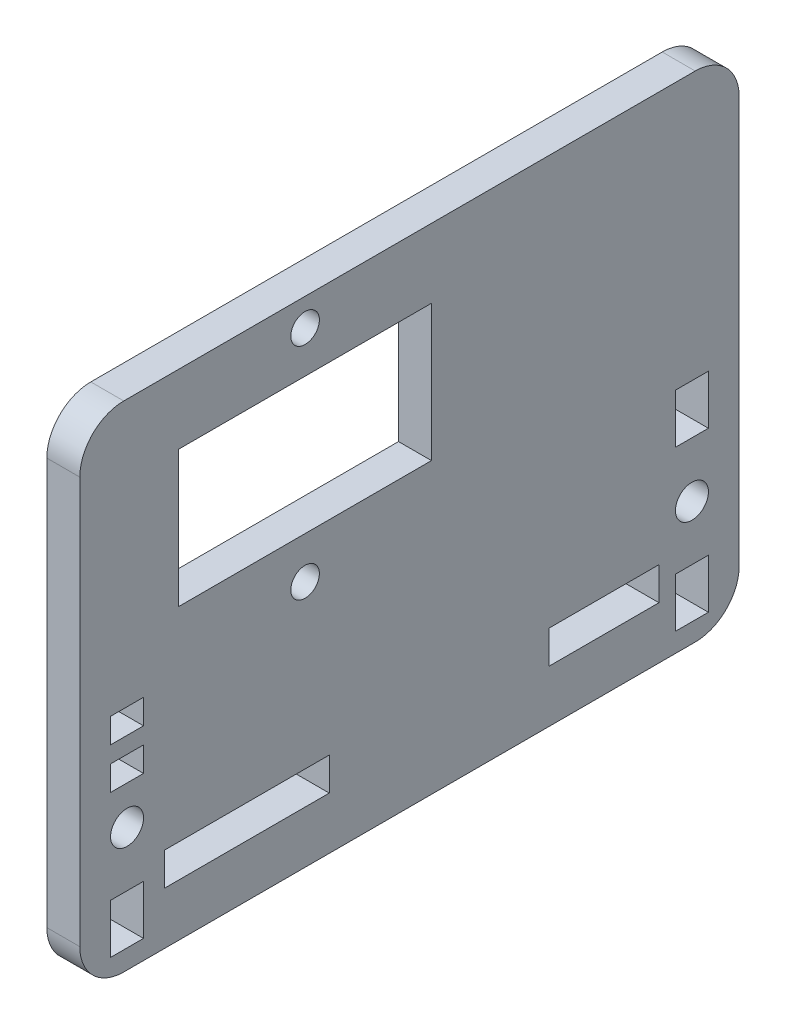
SolidWorks part; units mm, degrees
material "Acrílico (médio-alto impacto)"
ref_plane "Plano frontal" through (0, 0, 0) normal (0, 0, 1) x (1, 0, 0)
ref_plane "Plano superior" through (0, 0, 0) normal (0, 1, 0) x (1, 0, 0)
ref_plane "Plano direito" through (0, 0, 0) normal (1, 0, 0) x (0, 0, -1)
sketch "Esboço1" plane through (0, 0, 0) normal (1, 0, 0) x (0, 0, -1)
  line L1 (-30, -22.5) -> (30, -22.5)
  line L2 (-30, -22.5) -> (-30, 22.5)
  line L3 (-30, 22.5) -> (30, 22.5)
  line L4 (30, -22.5) -> (30, 22.5)
  point P7 (0, -22.5)
  point P9 (-30, 0)
  dimension "D1" = 45
  dimension "D2" = 60
sketch "Esboço9" plane through (0, 0, 0) normal (1, 0, 0) x (0, 0, -1)
  line L0 (-27.2, -18.5) -> (-24.2, -18.5) construction
  line L1 (-27.2, -20.75) -> (-24.2, -20.75)
  line L2 (-27.2, -20.75) -> (-27.2, -16.25)
  line L3 (-27.2, -16.25) -> (-24.2, -16.25)
  line L4 (-24.2, -20.75) -> (-24.2, -16.25)
  line L5 (-30, -22.5) -> (30, -22.5) construction
  line L7 (-25.7, -18.5) -> (-25.7, -11.25) construction
  line L8 (-25.7, -11.25) -> (-13.1725, -11.25) construction
  line L9 (-27.2, -1.75) -> (-24.2, -1.75)
  line L10 (-27.2, -1.75) -> (-27.2, -4)
  line L11 (-27.2, -4) -> (-24.2, -4)
  line L12 (-24.2, -1.75) -> (-24.2, -4)
  line L13 (0, 0) -> (0, -28.8435) construction
  line L14 (-27.2, -5.5) -> (-24.2, -5.5)
  line L15 (-27.2, -5.5) -> (-27.2, -7.75)
  line L16 (-27.2, -7.75) -> (-24.2, -7.75)
  line L17 (-24.2, -5.5) -> (-24.2, -7.75)
  line L18 (24.2, -16.25) -> (27.2, -16.25)
  line L19 (24.2, -16.25) -> (24.2, -20.75)
  line L20 (24.2, -20.75) -> (27.2, -20.75)
  line L21 (27.2, -16.25) -> (27.2, -20.75)
  line L22 (24.2, -1.75) -> (27.2, -1.75)
  line L23 (24.2, -1.75) -> (24.2, -6.25)
  line L24 (24.2, -6.25) -> (27.2, -6.25)
  line L25 (27.2, -1.75) -> (27.2, -6.25)
  point P24 (25.7, -11.25)
  dimension "D1" = 3
  dimension "D2" = 4.5
  dimension "D3" = 51.4
  dimension "D4" = 11.25
  dimension "D5" = 19
  dimension "D6" = 2.25
  dimension "D7" = 6
  dimension "D8" = 4.5
sketch "Esboço6" plane through (0, 0, 0) normal (1, 0, 0) x (0, 0, -1)
  line L0 (-24, -17.75) -> (24, -17.75) construction
  line L1 (-7.3, -14.75) -> (-22.3, -14.75)
  line L2 (-7.3, -14.75) -> (-7.3, -17.75)
  line L3 (-7.3, -17.75) -> (-22.3, -17.75)
  line L4 (-22.3, -14.75) -> (-22.3, -17.75)
  line L5 (22.7, -14.75) -> (12.7, -14.75)
  line L6 (22.7, -14.75) -> (22.7, -17.75)
  line L7 (22.7, -17.75) -> (12.7, -17.75)
  line L8 (12.7, -14.75) -> (12.7, -17.75)
  line L12 (0, 0) -> (0, -28.8435) construction
  line L14 (24.2, -20.75) -> (27.2, -20.75) construction
  line L15 (-16, -17.75) -> (-16, 10.2147) construction
  point P13 (0, -17.75)
  dimension "D1" = 3
  dimension "D2" = 1.7
  dimension "D3" = 15
  dimension "D4" = 10
  dimension "D5" = 1.3
  dimension "D6" = 48
  dimension "D7" = 7.3
  dimension "D8" = 12.7
  dimension "D9" = 3
  dimension "D10" = 8
ref_plane "Posicionamento base" through (0, -17.75, 0) normal (0, -1, 0) x (0, 0, -1)
extrude "Ressalto-extrusão1" add sketch "Esboço1" along normal blind 3
hole_wizard "Furo de diâmetro Ø3.0 (3)1" positions "Esboço7" profile "Esboço8" hole size "Ø3.0" standard "ISO" end condition through all
sketch "Esboço7" plane through (3, 0, 0) normal (1, 0, 0) x (0, 0, -1)
  point P0 (-25.7, -11.25)
  point P11 (25.7, -11.25)
sketch "Esboço8" plane through (3, -11.25, 25.7) normal (0, 1, 0) x (0, 0, -1)
  line L0 (0, 0) -> (0, 3)
  line L1 (0, 3) -> (1.5, 3)
  line L2 (1.5, 3) -> (1.5, 0)
  line L5 (1.5, 0) -> (0, 0)
  line L11 (0, -6.35) -> (0, 107.95) construction
  dimension "Thru Hole Dia." = 3
  dimension "Thru Hole Depth" = 3
extrude "Corte-extrusão2" cut sketch "Esboço9" along normal through all contours L11 L12 L9 L10 | L14 L17 L16 L15 | L4 L3 L2 L1
sketch "Perfil Corte" plane through (3, -11.3231, -32.0169) normal (1, 0, 0) x (0, 0, -1)
  line L0 (-41.5169, 11.3231) -> (-41.5169, 31.3231) construction
  line L1 (-53.0169, 15.1231) -> (-30.0169, 15.1231)
  line L2 (-53.0169, 15.1231) -> (-53.0169, 27.5231)
  line L3 (-53.0169, 27.5231) -> (-30.0169, 27.5231)
  line L4 (-30.0169, 15.1231) -> (-30.0169, 27.5231)
  line L5 (-41.5169, 27.5231) -> (-41.5169, 15.1231) construction
  line L6 (-53.0169, 21.3231) -> (-30.0169, 21.3231) construction
  line L7 (-30.0169, 21.3231) -> (-62.0169, 21.3231) construction
  line L8 (-62.0169, 33.8231) -> (-62.0169, -11.1769) construction
  line L9 (-2.0169, 33.8231) -> (-62.0169, 33.8231) construction
  line L13 (-62.0169, 33.8231) -> (-62.0169, -11.1769) construction
  point P0 (-41.5169, 21.3231)
  point P7 (-41.5169, 21.3231)
  dimension "D1" = 23
  dimension "entre furos" = 20
  dimension "D2" = 12.4
  dimension "Afastamento Lateral" = 20.5
  dimension "Posicionamento Altura" = 12.5
extrude "Corte Principal" cut sketch "Perfil Corte" against normal through all
hole_wizard "Furo de diâmetro Ø2.6 (2.6)1" positions "Esboço4" profile "Esboço5" hole size "Ø2.6" standard "ISO" end condition through all
sketch "Esboço4" plane through (3, -5, 96.5042) normal (1, 0, 0) x (0, 0, -1)
  point P0 (87.0042, 25)
  point P3 (87.0042, 5)
sketch "Esboço5" plane through (3, 20, 9.5) normal (0, 1, 0) x (0, 0, -1)
  line L0 (0, 0) -> (0, 3)
  line L1 (0, 3) -> (1.3, 3)
  line L2 (1.3, 3) -> (1.3, 0)
  line L5 (1.3, 0) -> (0, 0)
  line L11 (0, -6.35) -> (0, 107.95) construction
  dimension "Thru Hole Dia." = 2.6
  dimension "Thru Hole Depth" = 3
other "Furos Motor<1>"
fillet "Filete1" radius 4 4 edges at (1.5, 22.5, -30) (1.5, -22.5, -30) (1.5, -22.5, 30) (1.5, 22.5, 30)
extrude "Corte-extrusão1" cut sketch "Esboço6" along normal through all
